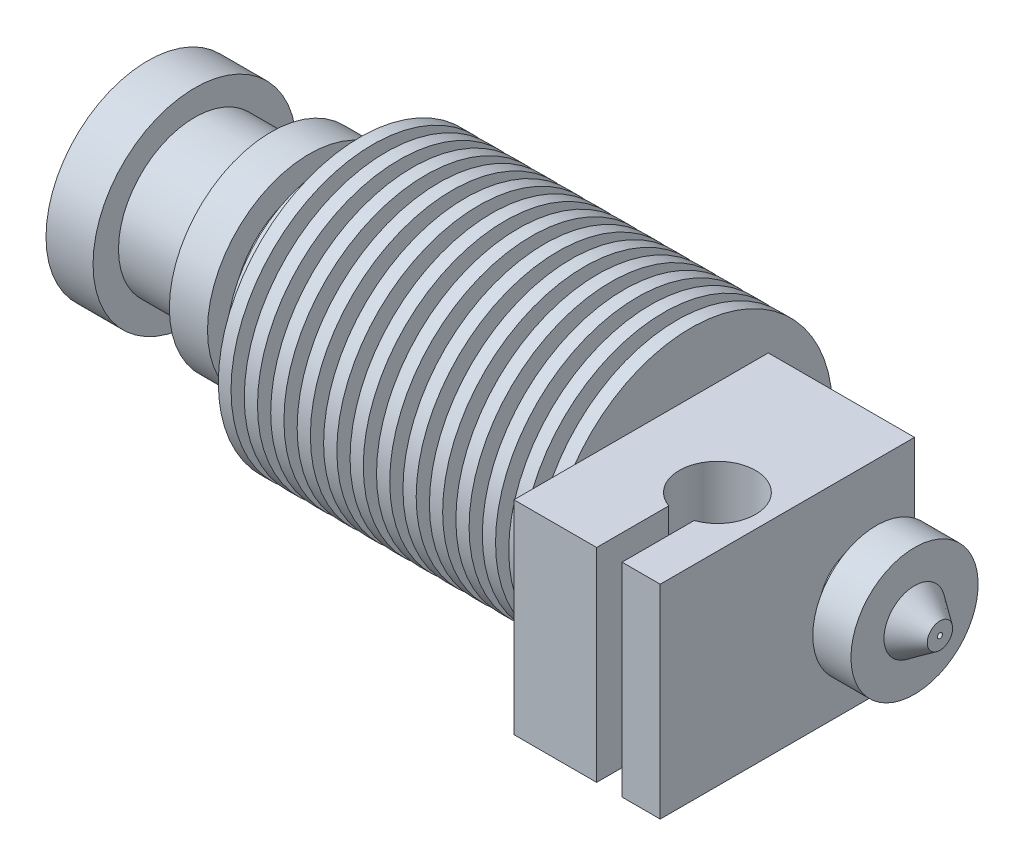
SolidWorks part; units mm, degrees
ref_plane "Front Plane" through (0, 0, 0) normal (0, 0, 1) x (1, 0, 0)
ref_plane "Top Plane" through (0, 0, 0) normal (0, 1, 0) x (1, 0, 0)
ref_plane "Right Plane" through (0, 0, 0) normal (1, 0, 0) x (0, 0, -1)
sketch "Sketch1" plane through (0, 0, 0) normal (0, 0, 1) x (1, 0, 0)
  line L0 (0, 0) -> (42.7, 0) construction
  line L1 (0, 2.1) -> (27.9, 2.1)
  line L2 (0, 2.1) -> (0, 8)
  line L3 (16.7, 11.15) -> (17.7, 11.15)
  line L4 (42.7, 11.15) -> (42.7, 3.5)
  line L5 (0, 8) -> (3.7, 8)
  line L6 (16.7, 6) -> (16.7, 11.15)
  line L7 (3.7, 8) -> (3.7, 6)
  line L8 (3.7, 6) -> (9.7, 6)
  line L9 (9.7, 6) -> (9.7, 8)
  line L10 (9.7, 8) -> (12.7, 8)
  line L11 (12.7, 8) -> (12.7, 6)
  line L12 (12.7, 6) -> (14.2, 6)
  line L13 (14.2, 6) -> (14.2, 8)
  line L14 (14.2, 8) -> (15.2, 8)
  line L15 (15.2, 8) -> (15.2, 6)
  line L16 (15.2, 6) -> (16.7, 6)
  line L17 (41.62, 9) -> (40.58, 9)
  line L18 (17.7, 11.15) -> (17.7, 9)
  line L19 (18.74, 11.15) -> (18.74, 9)
  line L20 (19.78, 11.15) -> (19.78, 9)
  line L21 (20.82, 11.15) -> (20.82, 9)
  line L22 (21.86, 11.15) -> (21.86, 9)
  line L23 (22.9, 11.15) -> (22.9, 9)
  line L24 (23.94, 11.15) -> (23.94, 9)
  line L25 (24.98, 11.15) -> (24.98, 9)
  line L26 (26.02, 11.15) -> (26.02, 9)
  line L27 (27.06, 11.15) -> (27.06, 9)
  line L28 (28.1, 11.15) -> (28.1, 9)
  line L29 (29.14, 11.15) -> (29.14, 9)
  line L30 (30.18, 11.15) -> (30.18, 9)
  line L31 (31.22, 11.15) -> (31.22, 9)
  line L32 (32.26, 11.15) -> (32.26, 9)
  line L33 (33.3, 11.15) -> (33.3, 9)
  line L34 (34.34, 11.15) -> (34.34, 9)
  line L35 (35.38, 11.15) -> (35.38, 9)
  line L36 (36.42, 11.15) -> (36.42, 9)
  line L37 (37.46, 11.15) -> (37.46, 9)
  line L38 (38.5, 11.15) -> (38.5, 9)
  line L39 (39.54, 11.15) -> (39.54, 9)
  line L40 (40.58, 11.15) -> (40.58, 9)
  line L41 (41.62, 11.15) -> (41.62, 9)
  line L42 (18.74, 11.15) -> (19.78, 11.15)
  line L43 (18.74, 9) -> (17.7, 9)
  line L44 (20.82, 11.15) -> (21.86, 11.15)
  line L45 (20.82, 9) -> (19.78, 9)
  line L46 (22.9, 11.15) -> (23.94, 11.15)
  line L47 (22.9, 9) -> (21.86, 9)
  line L48 (24.98, 11.15) -> (26.02, 11.15)
  line L49 (24.98, 9) -> (23.94, 9)
  line L50 (27.06, 11.15) -> (28.1, 11.15)
  line L51 (27.06, 9) -> (26.02, 9)
  line L52 (29.14, 11.15) -> (30.18, 11.15)
  line L53 (29.14, 9) -> (28.1, 9)
  line L54 (31.22, 11.15) -> (32.26, 11.15)
  line L55 (31.22, 9) -> (30.18, 9)
  line L56 (33.3, 11.15) -> (34.34, 11.15)
  line L57 (33.3, 9) -> (32.26, 9)
  line L58 (35.38, 11.15) -> (36.42, 11.15)
  line L59 (35.38, 9) -> (34.34, 9)
  line L60 (37.46, 11.15) -> (38.5, 11.15)
  line L61 (37.46, 9) -> (36.42, 9)
  line L62 (39.54, 11.15) -> (40.58, 11.15)
  line L63 (39.54, 9) -> (38.5, 9)
  line L64 (41.62, 11.15) -> (42.7, 11.15)
  line L65 (42.7, 3.5) -> (27.9, 3.5)
  line L66 (27.9, 3.5) -> (27.9, 2.1)
  dimension "D1" = 42.7
  dimension "D2" = 2.1
  dimension "D3" = 11.15
  dimension "D4" = 26
  dimension "D5" = 8
  dimension "D6" = 3.7
  dimension "D7" = 6
  dimension "D8" = 6
  dimension "D9" = 3
  dimension "D10" = 1
  dimension "D11" = 1.5
  dimension "D12" = 1
  dimension "D14" = 1.04
  dimension "D15" = 9
  dimension "D16" = 14.8
  dimension "D17" = 3.5
  dimension "D13" = 24
revolve "Revolve1" add sketch "Sketch1" angle 360 about L0
sketch "Sketch2" plane through (0, 0, 0) normal (0, 0, 1) x (1, 0, 0)
  line L0 (27.9, 0) -> (49.8, 0) construction
  line L1 (27.9, -2.1) -> (27.9, 2.1) construction
  line L2 (42.7, -11.15) -> (42.7, 11.15) construction
  line L3 (42.7, 0.5) -> (49.8, 0.5)
  line L4 (49.8, 0.5) -> (49.8, 3)
  line L5 (49.8, 3) -> (44.8, 3)
  line L6 (44.8, 3) -> (44.8, 1.4)
  line L7 (44.8, 1.4) -> (42.7, 1.4)
  line L8 (42.7, 1.4) -> (42.7, 3.5)
  line L9 (42.7, 3.5) -> (27.9, 3.5)
  line L10 (27.9, 3.5) -> (27.9, 0.5)
  line L11 (27.9, 0.5) -> (42.7, 0.5)
  dimension "D1" = 7.1
  dimension "D2" = 2.1
  dimension "D3" = 1.4
  dimension "D4" = 3
  dimension "D5" = 1
revolve "Revolve2" add sketch "Sketch2" angle 360 about L0
sketch "Sketch3" plane through (49.8, 0, 0) normal (1, 0, 0) x (0, 0, -1)
  line L1 (-15.5, 8) -> (4.5, 8)
  line L2 (-15.5, 8) -> (-15.5, -8)
  line L3 (-15.5, -8) -> (4.5, -8)
  line L4 (4.5, 8) -> (4.5, -8)
  circle A0 centre (0, 0) radius 3
  circle A1 centre (0, 0) radius 3 construction
  dimension "D1" = 16
  dimension "D2" = 8
  dimension "D3" = 4.5
  dimension "D4" = 20
extrude "Boss-Extrude1" add sketch "Sketch3" along normal blind 6 and the other way blind 5.5
sketch "Sketch4" plane through (0, 0, 0) normal (0, 0, 1) x (1, 0, 0)
  line L0 (0, 0) -> (55.8, 0) construction
  line L1 (0, 8) -> (0, -8) construction
  line L2 (55.8, 8) -> (55.8, -8) construction
  line L3 (49.8, 0.2) -> (62.3, 0.2)
  line L4 (62.3, 0.2) -> (62.3, 1)
  line L5 (60.3, 2.4004) -> (60.3, 5)
  line L6 (60.3, 5) -> (57.3, 5)
  line L7 (57.3, 5) -> (57.3, 3)
  line L8 (57.3, 3) -> (49.8, 3)
  line L9 (49.8, 3) -> (49.8, 0.2)
  line L10 (62.3, 1) -> (60.3, 2.4004)
  dimension "D1" = 3
  dimension "D2" = 125
  dimension "D3" = 1
  dimension "D4" = 0.2
  dimension "D5" = 10.5
  dimension "D6" = 6
  dimension "D7" = 7.5
  dimension "D8" = 5
  dimension "D9" = 2
revolve "Revolve3" add sketch "Sketch4" angle 360 about L0
sketch "Sketch5" plane through (0, 8, 0) normal (0, 1, 0) x (1, 0, 0)
  line L0 (50.8, -15.5) -> (52.8, -15.5)
  line L1 (44.3, -15.5) -> (55.8, -15.5) construction
  line L2 (52.8, -15.5) -> (52.8, -9.8284)
  line L3 (50.8, -15.5) -> (50.8, -9.8284)
  line L4 (55.8, 4.5) -> (55.8, -15.5) construction
  line L5 (44.3, 4.5) -> (55.8, 4.5) construction
  arc A0 (52.8, -9.8284) -> (50.8, -9.8284) centre (51.8, -7) ccw
  dimension "D3" = 3
  dimension "D1" = 4
  dimension "D2" = 11.5
  dimension "D4" = 2
extrude "Cut-Extrude1" cut sketch "Sketch5" against normal through all
